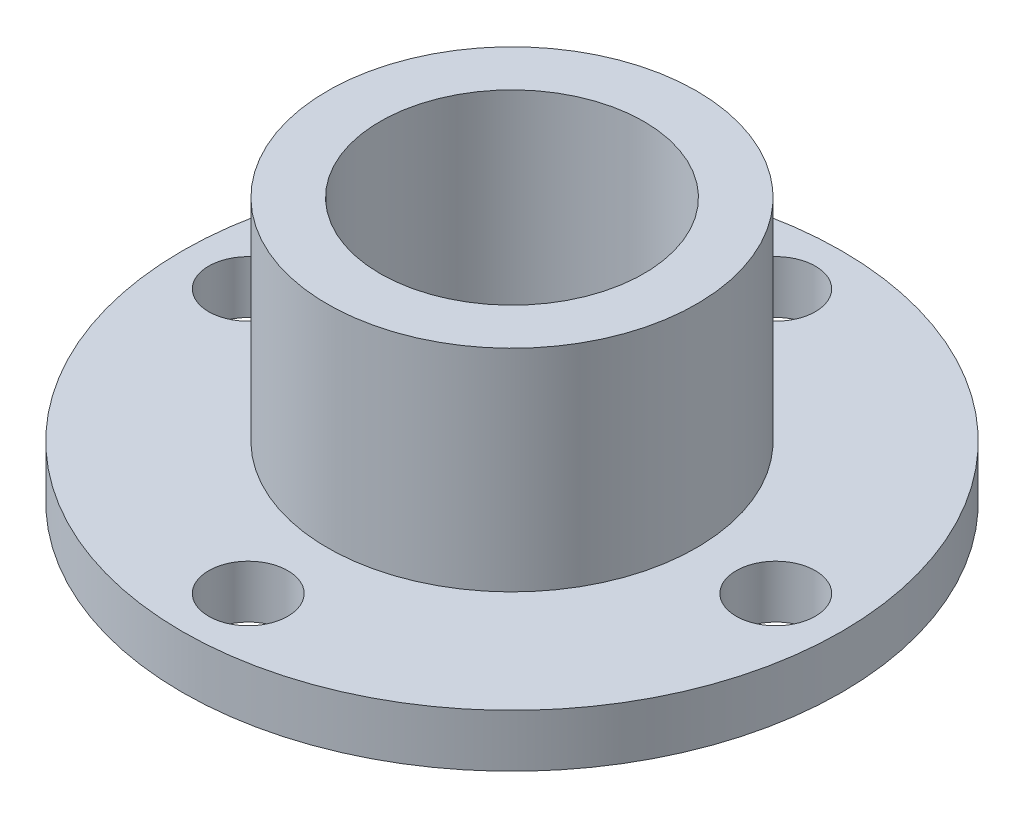
SolidWorks part; units mm, degrees
ref_plane "Front Plane" through (0, 0, 0) normal (0, 0, 1) x (1, 0, 0)
ref_plane "Top Plane" through (0, 0, 0) normal (0, 1, 0) x (1, 0, 0)
ref_plane "Right Plane" through (0, 0, 0) normal (1, 0, 0) x (0, 0, -1)
sketch "Sketch1" plane through (0, 0, 0) normal (1, 0, 0) x (0, 0, -1)
  line L0 (-5, 0) -> (-12.5, 0)
  line L1 (-12.5, 0) -> (-12.5, 2)
  line L2 (-12.5, 2) -> (-7, 2)
  line L3 (-7, 2) -> (-7, 10)
  line L4 (-7, 10) -> (-5, 10)
  line L5 (-5, 10) -> (-5, 0)
  line L6 (0, -0.9419) -> (0, 8.0756) construction
  dimension "D1" = 2
  dimension "D2" = 10
  dimension "D3" = 2
  dimension "D4" = 10
  dimension "D5" = 25
revolve "Revolve1" add sketch "Sketch1" angle 360 about L6
sketch "Sketch2" plane through (0, 2, 0) normal (0, 1, 0) x (1, 0, 0)
  line L0 (-2.4513, 5) -> (2.3915, 5) construction
  circle A0 centre (0, 10) radius 1.5
  circle A1 centre (0, 0) radius 5 construction
  circle A2 centre (10, 0) radius 1.5
  circle A3 centre (0, -10) radius 1.5
  circle A4 centre (-10, 0) radius 1.5
  point P3 (0, 0)
  point P7 (0, 0)
  point P9 (0, 0)
  dimension "D2" = 3
  dimension "D1" = 5
  dimension "D3" = 4
extrude "Cut-Extrude1" cut sketch "Sketch2" against normal up to next
